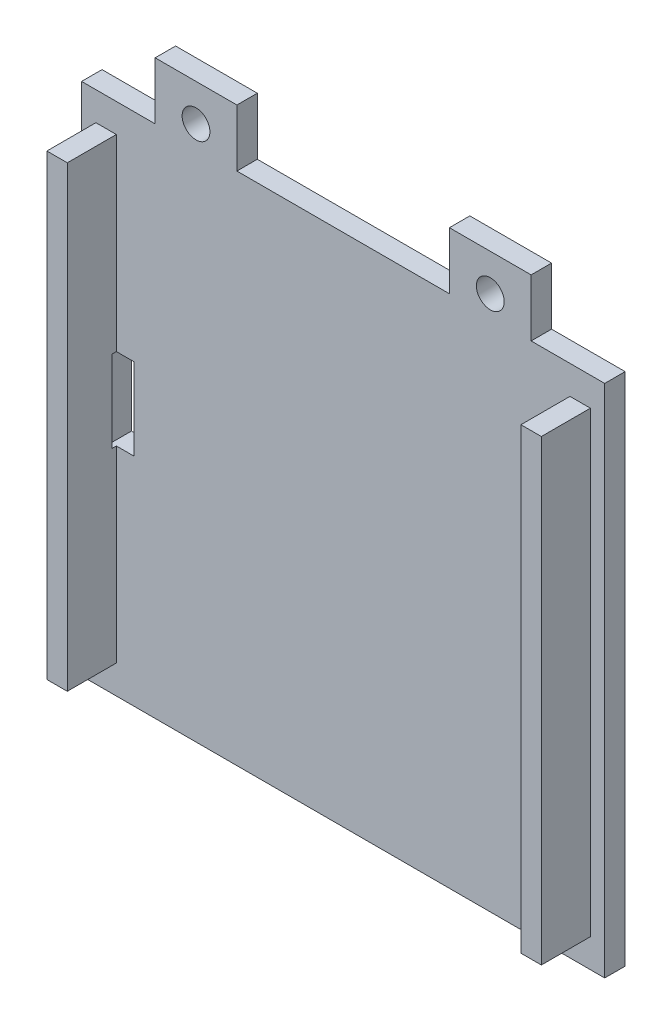
SolidWorks part; units mm, degrees
ref_plane "前视基准面" through (0, 0, 0) normal (0, 0, 1) x (1, 0, 0)
ref_plane "上视基准面" through (0, 0, 0) normal (0, 1, 0) x (1, 0, 0)
ref_plane "右视基准面" through (0, 0, 0) normal (1, 0, 0) x (0, 0, -1)
other "Configuration Table"
sketch "Sketch_Board_support_and_lugs" plane through (0, 0, 0) normal (0, 0, 1) x (1, 0, 0)
  line L0 (32, 31.5) -> (32, -31.5)
  line L1 (32, -31.5) -> (-32, -31.5)
  line L2 (-32, -31.5) -> (-32, 31.5)
  line L3 (-32, 31.5) -> (-23, 31.5)
  line L4 (-23, 31.5) -> (-23, 38.5)
  line L5 (-23, 38.5) -> (-13, 38.5)
  line L6 (-13, 38.5) -> (-13, 31.5)
  line L7 (-13, 31.5) -> (13, 31.5)
  line L8 (13, 31.5) -> (13, 38.5)
  line L9 (13, 38.5) -> (23, 38.5)
  line L10 (23, 38.5) -> (23, 31.5)
  line L11 (23, 31.5) -> (32, 31.5)
extrude "Board_support_and_lugs" add sketch "Sketch_Board_support_and_lugs" along normal blind 2.5 from offset 0
sketch "Sketch_PCB_edge_stops" plane through (0, 0, 0) normal (0, 0, 1) x (1, 0, 0)
  line L0 (-30.25, -28) -> (-30.25, 28)
  line L1 (-30.25, 28) -> (-27.75, 28)
  line L2 (-27.75, 28) -> (-27.75, -28)
  line L3 (-27.75, -28) -> (-30.25, -28)
  line L4 (27.75, -28) -> (27.75, 28)
  line L5 (27.75, 28) -> (30.25, 28)
  line L6 (30.25, 28) -> (30.25, -28)
  line L7 (30.25, -28) -> (27.75, -28)
extrude "PCB_edge_stops" add sketch "Sketch_PCB_edge_stops" along normal blind 6 from offset 2.5
sketch "Sketch_Board_strap_slots" plane through (0, 0, 0) normal (0, 0, 1) x (1, 0, 0)
  line L0 (-28.4, -5) -> (-28.4, 5)
  line L1 (-28.4, 5) -> (-25.6, 5)
  line L2 (-25.6, 5) -> (-25.6, -5)
  line L3 (-25.6, -5) -> (-28.4, -5)
  line L4 (25.6, -5) -> (25.6, 5)
  line L5 (25.6, 5) -> (28.4, 5)
  line L6 (28.4, 5) -> (28.4, -5)
  line L7 (28.4, -5) -> (25.6, -5)
extrude "Board_strap_slots" cut sketch "Sketch_Board_strap_slots" along normal blind 4 from offset 1
sketch "Sketch_External_M3_mounts" plane through (0, 0, 0) normal (0, 0, 1) x (1, 0, 0)
  circle A0 centre (-18, 34) radius 1.7
  circle A1 centre (18, 34) radius 1.7
  dimension "D1" = 3.4
  dimension "D4" = 3.4
  dimension "D2" = 18
  dimension "D3" = 34
  dimension "D5" = 18
  dimension "D6" = 34
extrude "External_M3_mounts" cut sketch "Sketch_External_M3_mounts" along normal blind 5 from offset 1
